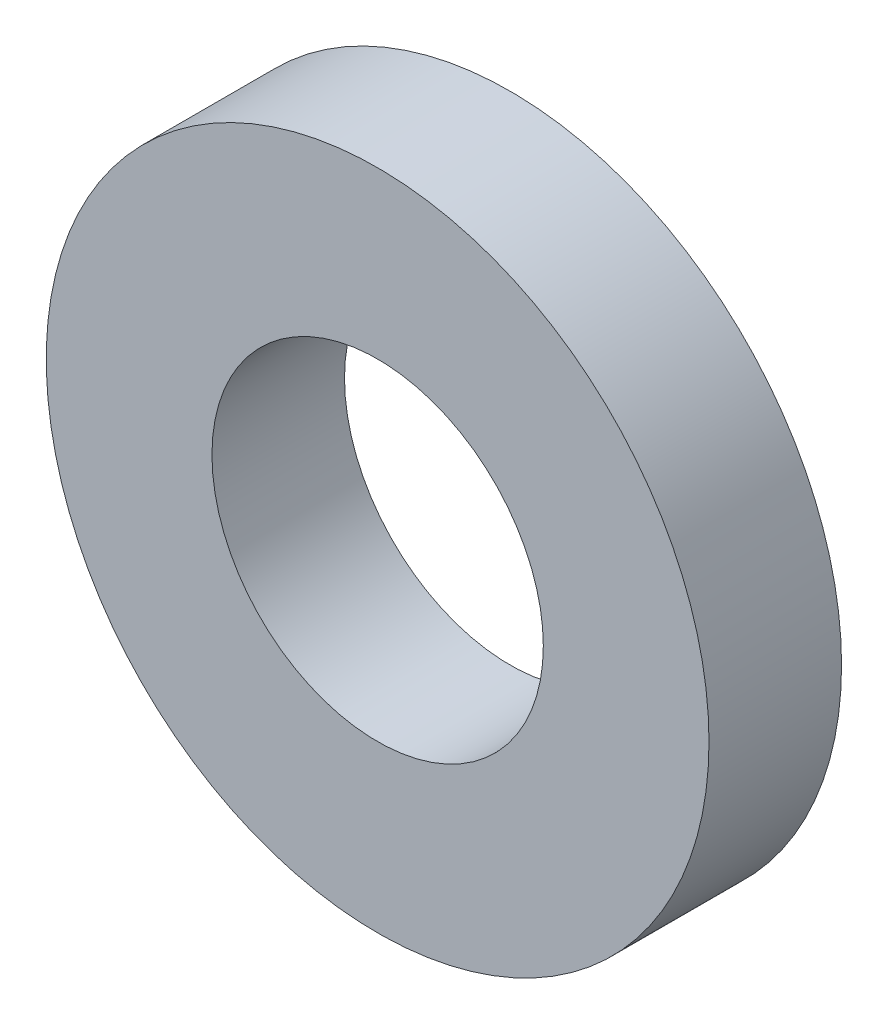
SolidWorks part; units mm, degrees
ref_plane "Front Plane" through (0, 0, 0) normal (0, 0, 1) x (1, 0, 0)
ref_plane "Top Plane" through (0, 0, 0) normal (0, 1, 0) x (1, 0, 0)
ref_plane "Right Plane" through (0, 0, 0) normal (1, 0, 0) x (0, 0, -1)
sketch "Sketch1" plane through (0, 0, 0) normal (0, 0, 1) x (1, 0, 0)
  circle A0 centre (0, 0) radius 2.5
  circle A1 centre (0, 0) radius 5
  dimension "D1" = 5
  dimension "D2" = 2.5
extrude "Boss-Extrude1" add sketch "Sketch1" along normal blind 2
